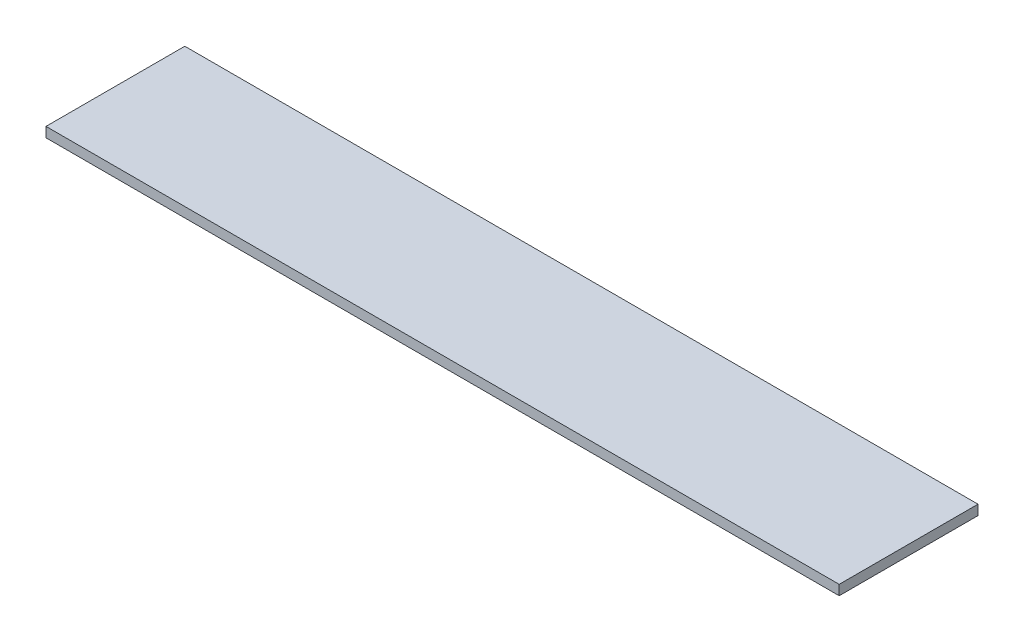
SolidWorks part; units mm, degrees
ref_plane "Front Plane" through (0, 0, 0) normal (0, 0, 1) x (1, 0, 0)
ref_plane "Top Plane" through (0, 0, 0) normal (0, 1, 0) x (1, 0, 0)
ref_plane "Right Plane" through (0, 0, 0) normal (1, 0, 0) x (0, 0, -1)
sketch "Sketch1" plane through (0, 0, 0) normal (0, 1, 0) x (1, 0, 0)
  line L1 (-127, -22.225) -> (127, -22.225)
  line L2 (-127, -22.225) -> (-127, 22.225)
  line L3 (-127, 22.225) -> (127, 22.225)
  line L4 (127, -22.225) -> (127, 22.225)
  line L5 (-127, -22.225) -> (127, 22.225) construction
  line L6 (-127, 22.225) -> (127, -22.225) construction
  point P0 (0, 0)
  dimension "D1" = 44.45
  dimension "D2" = 254
extrude "Boss-Extrude1" add sketch "Sketch1" along normal blind 3.175
